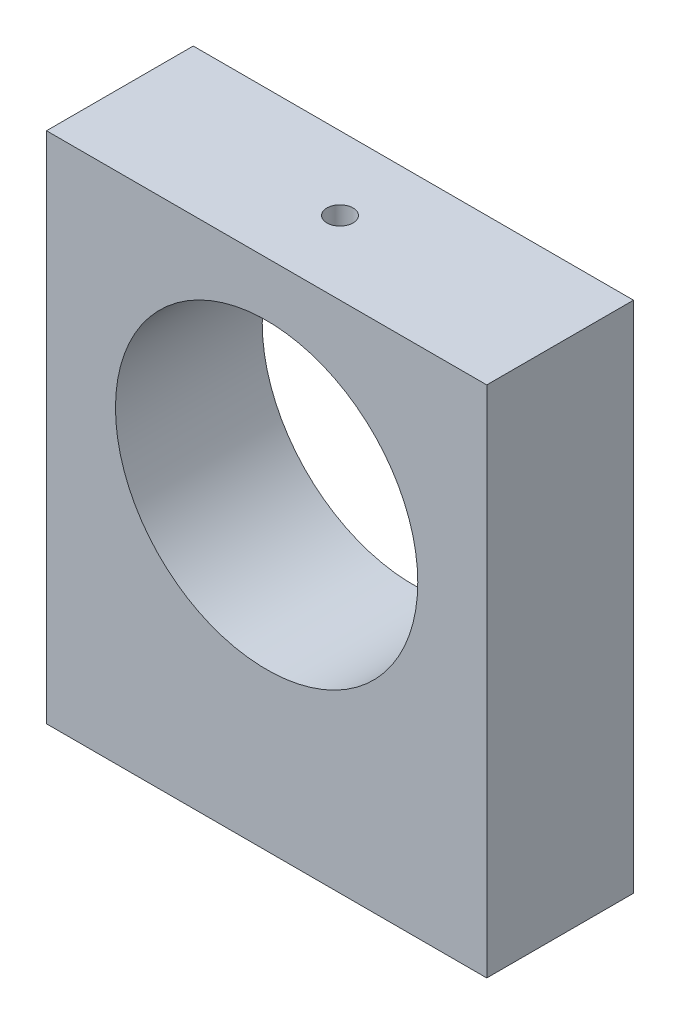
SolidWorks part; units mm, degrees
material "1060 Alloy"
ref_plane "Front Plane" through (0, 0, 0) normal (0, 0, 1) x (1, 0, 0)
ref_plane "Top Plane" through (0, 0, 0) normal (0, 1, 0) x (1, 0, 0)
ref_plane "Right Plane" through (0, 0, 0) normal (1, 0, 0) x (0, 0, -1)
sketch "Sketch1" plane through (0, 0, 0) normal (0, 0, 1) x (1, 0, 0)
  line L0 (19.05, 0) -> (-19.05, 0)
  line L3 (-19.05, 0) -> (-19.05, 44.45)
  line L4 (-19.05, 44.45) -> (19.05, 44.45)
  line L5 (0, 44.45) -> (0, 0) construction
  line L6 (19.05, 0) -> (19.05, 44.45)
  line L9 (-7.5, 26.67) -> (7.5, 26.67) construction
  line L10 (-7.5, 18.448) -> (-7.5, 34.892) construction
  line L11 (7.5, 34.892) -> (7.5, 18.448) construction
  circle A0 centre (0, 26.67) radius 13.081
  point P13 (0, 13.589)
  dimension "D5" = 26.162
  dimension "D3" = 44.45
  dimension "D4" = 19.05
extrude "Boss-Extrude1" add sketch "Sketch1" along normal blind 12.7
hole_wizard "#4-40 Tapped Hole1" positions "Sketch6" profile "Sketch5" tap size "#4-40" standard "Ansi Inch"
sketch "Sketch6" plane through (0, 44.45, 0) normal (0, 1, 0) x (-1, 0, 0)
  line L0 (19.05, 6.35) -> (-19.05, 6.35) construction
  line L1 (19.05, 12.7) -> (19.05, 0) construction
  line L2 (-19.05, 12.7) -> (-19.05, 0) construction
  point P0 (0, 6.35)
sketch "Sketch5" plane through (0, 44.45, 6.35) normal (1, 0, 0) x (0, 0, 1)
  line L0 (0, 0) -> (0, 18.4582)
  line L1 (0, 18.4582) -> (1.1303, 17.779)
  line L2 (1.1303, 17.779) -> (1.1303, 0)
  line L5 (1.1303, 0) -> (0, 0)
  line L10 (0, 18.4582) -> (-1.1303, 17.779) construction
  line L11 (0, -6.35) -> (0, 107.95) construction
  dimension "Tap Drill Dia." = 2.2606
  dimension "Tap Drill Depth" = 17.779
  dimension "Drill Angle" = 118
cosmetic thread "Hole Thread3" parameters "D1"=5.1304, "D2"=2.8448
hole_wizard "#10-32 Tapped Hole1" positions "Sketch8" profile "Sketch7" tap size "#10-32" standard "Ansi Inch"
sketch "Sketch8" plane through (0, 0, 0) normal (0, -1, 0) x (1, 0, 0)
  line L1 (-19.05, 6.35) -> (19.05, 6.35) construction
  line L2 (-19.05, 12.7) -> (-19.05, 0) construction
  line L3 (19.05, 12.7) -> (19.05, 0) construction
  point P0 (-12.7, 6.35)
  point P12 (12.7, 6.35)
  dimension "D1" = 6.35
  dimension "D2" = 6.35
sketch "Sketch7" plane through (-12.7, 0, 6.35) normal (1, 0, 0) x (0, 0, -1)
  line L0 (0, 0) -> (0, 13.9133)
  line L1 (0, 13.9133) -> (2.0193, 12.7)
  line L2 (2.0193, 12.7) -> (2.0193, 0)
  line L5 (2.0193, 0) -> (0, 0)
  line L10 (0, 13.9133) -> (-2.0193, 12.7) construction
  line L11 (0, -6.35) -> (0, 107.95) construction
  dimension "Tap Drill Dia." = 4.0386
  dimension "Tap Drill Depth" = 12.7
  dimension "Drill Angle" = 118
cosmetic thread "Hole Thread4" parameters "D1"=9.652, "D2"=4.826
cosmetic thread "Hole Thread5" parameters "D1"=9.652, "D2"=4.826
